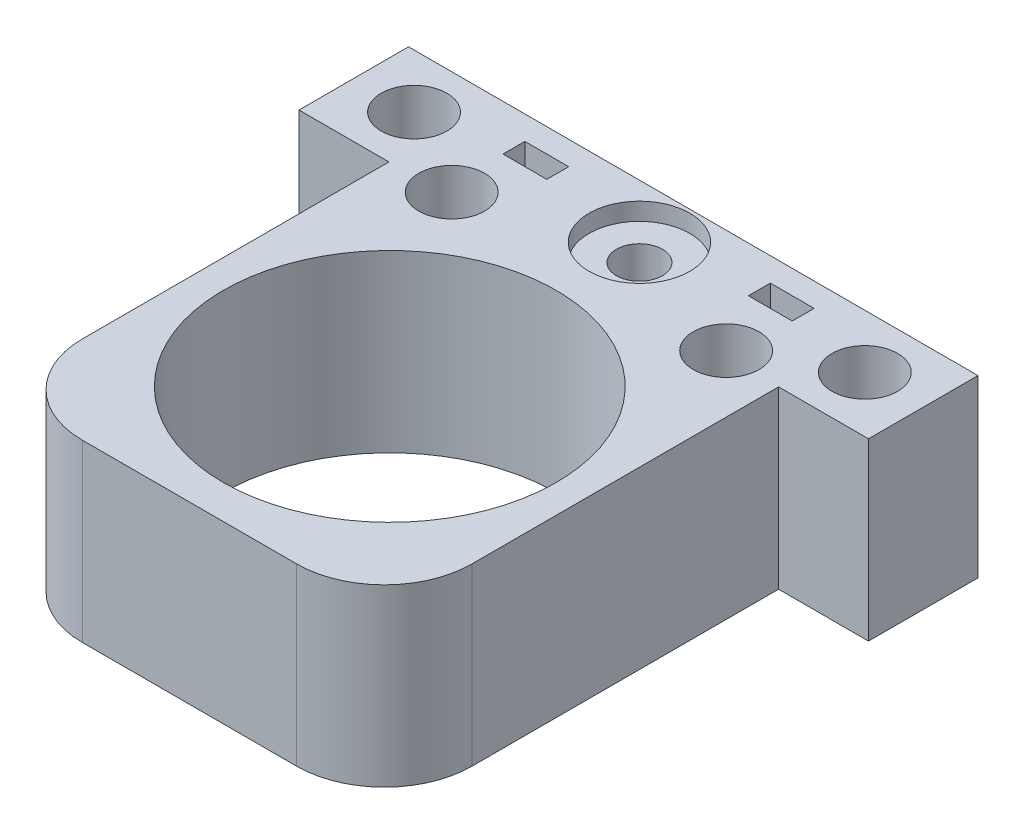
SolidWorks part; units mm, degrees
ref_plane "Front Plane" through (0, 0, 0) normal (0, 0, 1) x (1, 0, 0)
ref_plane "Top Plane" through (0, 0, 0) normal (0, 1, 0) x (1, 0, 0)
ref_plane "Right Plane" through (0, 0, 0) normal (1, 0, 0) x (0, 0, -1)
sketch "Sketch1" plane through (0, 0, 0) normal (0, 1, 0) x (1, 0, 0)
  line L0 (0, 0) -> (0, -45) construction
  line L1 (-65, 25) -> (65, 25)
  line L2 (-65, 25) -> (-65, -25)
  line L3 (-65, -25) -> (-32.8976, -25)
  line L4 (65, 25) -> (65, -25)
  line L5 (-65, 25) -> (65, -25) construction
  line L6 (-65, -25) -> (65, 25) construction
  line L7 (32.8976, -25) -> (65, -25)
  arc A0 (32.8976, -25) -> (-32.8976, -25) centre (0, -45) ccw
  point P0 (0, 0)
  dimension "D4" = 77
  dimension "D1" = 50
  dimension "D2" = 130
  dimension "D3" = 45
extrude "Boss-Extrude1" add sketch "Sketch1" along normal blind 60
sketch "Sketch2" plane through (0, 60, 0) normal (0, 1, 0) x (1, 0, 0)
  line L0 (0, -6.5) -> (0, 25) construction
  line L1 (65, 25) -> (-65, 25) construction
  circle A0 centre (-51.4526, 12.7142) radius 7.5
  arc A1 (32.8976, -25) -> (-32.8976, -25) centre (0, -45) ccw construction
  circle A2 centre (51.4526, 12.7142) radius 7.5
  dimension "D1" = 15
extrude "Cut-Extrude1" cut sketch "Sketch2" against normal blind 60
sketch "Sketch3" plane through (0, 60, 0) normal (0, 1, 0) x (1, 0, 0)
  line L0 (0, -6.5) -> (0, 25) construction
  line L1 (65, 25) -> (-65, 25) construction
  line L2 (-51.4526, 12.7142) -> (51.4526, 12.7142) construction
  arc A0 (32.8976, -25) -> (-32.8976, -25) centre (0, -45) ccw construction
  circle A1 centre (0, 12.7142) radius 5.25
  dimension "D1" = 10.5
extrude "Cut-Extrude2" cut sketch "Sketch3" against normal blind 60
sketch "Sketch4" plane through (0, 60, 0) normal (0, 1, 0) x (1, 0, 0)
  circle A0 centre (0, 12.7142) radius 11.5
  dimension "D1" = 23
extrude "Cut-Extrude3" cut sketch "Sketch4" against normal blind 4
sketch "Sketch5" plane through (0, 60, 0) normal (0, 1, 0) x (1, 0, 0)
  line L0 (0, 25) -> (0, -6.5) construction
  line L1 (-57.8842, -14.0803) -> (-47.8842, -14.0803)
  line L2 (-57.8842, -14.0803) -> (-57.8842, -19.0803)
  line L3 (-57.8842, -19.0803) -> (-47.8842, -19.0803)
  line L4 (-47.8842, -14.0803) -> (-47.8842, -19.0803)
  line L5 (65, 25) -> (-65, 25) construction
  line L6 (-33.0131, 19.5794) -> (-23.0131, 19.5794)
  line L7 (-33.0131, 19.5794) -> (-33.0131, 14.5794)
  line L8 (-33.0131, 14.5794) -> (-23.0131, 14.5794)
  line L9 (-23.0131, 19.5794) -> (-23.0131, 14.5794)
  line L10 (57.8842, -19.0803) -> (47.8842, -19.0803)
  line L11 (47.8842, -14.0803) -> (47.8842, -19.0803)
  line L12 (57.8842, -14.0803) -> (47.8842, -14.0803)
  line L13 (57.8842, -14.0803) -> (57.8842, -19.0803)
  line L14 (33.0131, 19.5794) -> (33.0131, 14.5794)
  line L15 (33.0131, 14.5794) -> (23.0131, 14.5794)
  line L16 (23.0131, 19.5794) -> (23.0131, 14.5794)
  line L17 (33.0131, 19.5794) -> (23.0131, 19.5794)
  arc A0 (32.8976, -25) -> (-32.8976, -25) centre (0, -45) ccw construction
  dimension "D1" = 5
  dimension "D2" = 10
extrude "Cut-Extrude4" cut sketch "Sketch5" against normal blind 60
sketch "Sketch6" plane through (0, 60, 0) normal (0, 1, 0) x (1, 0, 0)
  line L0 (-65, 25) -> (-65, -25) construction
  line L1 (-65, 0) -> (65, 0)
  line L2 (-65, 0) -> (-65, -90)
  line L3 (-65, -90) -> (65, -90)
  line L4 (65, 0) -> (65, -90)
  dimension "D1" = 90
extrude "Boss-Extrude2" add sketch "Sketch6" against normal blind 60
sketch "Sketch7" plane through (0, 60, 0) normal (0, 1, 0) x (1, 0, 0)
  line L0 (0, 12.7142) -> (0, -44.2858) construction
  circle A0 centre (0, -44.2858) radius 38
  dimension "D2" = 76
  dimension "D1" = 57
extrude "Cut-Extrude5" cut sketch "Sketch7" against normal blind 60
sketch "Sketch8" plane through (0, 0, 0) normal (0, -1, 0) x (1, 0, 0)
  line L1 (-65, 90) -> (65, 90)
  line L2 (-65, 90) -> (-65, -25)
  line L3 (-65, -25) -> (65, -25)
  line L4 (65, 90) -> (65, -25)
extrude "Cut-Extrude6" cut sketch "Sketch8" against normal blind 20
sketch "Sketch9" plane through (0, 60, 0) normal (0, 1, 0) x (1, 0, 0)
  line L0 (-65, 25) -> (-65, -90) construction
  line L1 (-65, 0) -> (-44.4744, 0)
  line L2 (-65, 0) -> (-65, -90)
  line L3 (-65, -90) -> (-44.4744, -90)
  line L4 (-44.4744, 0) -> (-44.4744, -90)
  line L5 (-65, -90) -> (65, -90) construction
  line L6 (0, 12.7142) -> (0, -90) construction
  line L7 (65, -90) -> (44.4744, -90)
  line L8 (44.4744, 0) -> (44.4744, -90)
  line L9 (65, 0) -> (44.4744, 0)
  line L10 (65, 0) -> (65, -90)
extrude "Cut-Extrude7" cut sketch "Sketch9" against normal blind 40
fillet "Fillet2" radius 20 2 edges at (44.4744, 40, 90) (-44.4744, 40, 90)
sketch "Sketch10" plane through (0, 60, 0) normal (0, 1, 0) x (1, 0, 0)
  line L0 (0, 12.7142) -> (0, -36.1521) construction
  circle A0 centre (-51.4526, 12.7142) radius 7.5
  circle A1 centre (-31.3268, 1.1804) radius 7.5
  circle A2 centre (31.3268, 1.1804) radius 7.5
extrude "Cut-Extrude8" cut sketch "Sketch10" against normal blind 40
